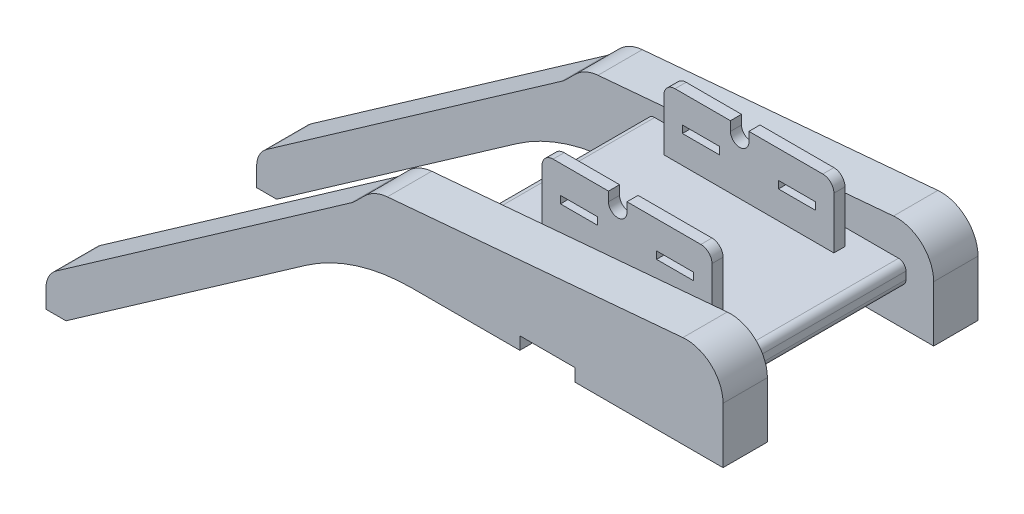
SolidWorks part; units mm, degrees
ref_plane "Front Plane" through (0, 0, 0) normal (0, 0, 1) x (1, 0, 0)
ref_plane "Top Plane" through (0, 0, 0) normal (0, 1, 0) x (1, 0, 0)
ref_plane "Right Plane" through (0, 0, 0) normal (1, 0, 0) x (0, 0, -1)
sketch "Sketch1" plane through (0, 0, 0) normal (0, 0, 1) x (1, 0, 0)
  line L1 (213.0197, -692.1049) -> (213.0197, -628.04)
  line L2 (248.221, -560.419) -> (1260.8984, 148.6653)
  line L3 (1277.8567, 162.8951) -> (1307.5066, 192.5449)
  line L5 (1470.2147, 0) -> (2540, 0)
  line L6 (2540, 0) -> (2540, 330.2)
  line L7 (1386.2404, 229.2591) -> (2540, 330.2)
  line L8 (281.5717, -692.1049) -> (1105.9937, -114.8385)
  line L9 (213.0197, -692.1049) -> (281.5717, -692.1049)
  arc A0 (1307.5066, 192.5449) -> (1386.2404, 229.2591) centre (1397.3091, 102.7424) cw
  arc A1 (1260.8984, 148.6653) -> (1277.8567, 162.8951) centre (1188.0541, 252.6976) ccw
  arc A2 (213.0197, -628.04) -> (248.221, -560.419) centre (295.5697, -628.04) cw
  arc A4 (1105.9937, -114.8385) -> (1470.2147, 0) centre (1470.2147, -635) cw
  point P13 (1270, 155.0384)
  point P18 (0, 0)
  point P22 (1270, 0)
  dimension "D8" = 127
  dimension "D9" = 82.55
  dimension "D12" = 635
  dimension "D1" = 1270
  dimension "D3" = 220
  dimension "D4" = 85
  dimension "D5" = 215
  dimension "D6" = 1270
  dimension "D7" = 330.2
  dimension "D11" = 127
extrude "Boss-Extrude1" add sketch "Sketch1" along normal blind 152.4
sketch "Sketch2" plane through (0, 0, 152.4) normal (0, 0, 1) x (1, 0, 0)
  line L0 (2540, 0) -> (2540, 330.2) construction
  line L1 (1841.5, -147.066) -> (2032, -147.066)
  line L2 (1841.5, -147.066) -> (1841.5, 43.434)
  line L3 (1841.5, 43.434) -> (2032, 43.434)
  line L4 (2032, -147.066) -> (2032, 43.434)
  line L5 (1841.5, -147.066) -> (2032, 43.434) construction
  line L6 (1841.5, 43.434) -> (2032, -147.066) construction
  line L7 (1470.2147, 0) -> (2540, 0) construction
  point P0 (1936.75, -51.816)
  dimension "D1" = 190.5
  dimension "D2" = 508
  dimension "D3" = 43.434
extrude "Cut-Extrude1" cut sketch "Sketch2" against normal blind 254
sketch "Sketch4" plane through (0, 0, 152.4) normal (0, 0, 1) x (1, 0, 0)
  line L0 (2540, 0) -> (2540, 330.2) construction
  line L1 (1581.15, 124.7896) -> (2419.35, 124.7896)
  line L2 (1555.75, 150.1896) -> (1555.75, 175.5896)
  line L3 (1581.15, 200.9896) -> (2419.35, 200.9896)
  line L4 (2444.75, 150.1896) -> (2444.75, 175.5896)
  line L5 (1555.75, 124.7896) -> (2444.75, 200.9896) construction
  line L6 (1555.75, 200.9896) -> (2444.75, 124.7896) construction
  line L8 (2540, 330.2) -> (1386.2404, 229.2591) construction
  arc A0 (2419.35, 124.7896) -> (2444.75, 150.1896) centre (2419.35, 150.1896) ccw
  arc A1 (2419.35, 200.9896) -> (2444.75, 175.5896) centre (2419.35, 175.5896) cw
  arc A2 (1581.15, 124.7896) -> (1555.75, 150.1896) centre (1581.15, 150.1896) cw
  arc A3 (1555.75, 175.5896) -> (1581.15, 200.9896) centre (1581.15, 175.5896) cw
  point P0 (2000.25, 162.8896)
  point P19 (1963.1202, 279.7296)
  dimension "D4" = 25.4
  dimension "D1" = 76.2
  dimension "D2" = 889
  dimension "D3" = 95.25
  dimension "D5" = 78.74
extrude "Boss-Extrude2" add sketch "Sketch4" along normal blind 571.5
ref_plane "Plane1" through (0, 0, 438.15) normal (0, 0, 1) x (1, 0, 0)
fillet "Fillet1" radius 127 1 edges at (2540, 330.2, 76.2)
mirror "Mirror1" about plane through (0, 0, 438.15) normal (0, 0, 1) of "Fillet1", "Cut-Extrude1", "Boss-Extrude1"
ref_plane "Plane2" through (0, 0, 247.65) normal (0, 0, 1) x (1, 0, 0)
sketch "Sketch8" plane through (0, 0, 247.65) normal (0, 0, 1) x (1, 0, 0)
  line L0 (2419.35, 200.9896) -> (1581.15, 200.9896) construction
  line L2 (1497.1384, 200.9896) -> (2375.4143, 200.9896) construction
  line L4 (1708.15, 200.9896) -> (1708.15, 378.7896)
  line L5 (1746.25, 416.8896) -> (2254.25, 416.8896)
  line L6 (2292.35, 378.7896) -> (2292.35, 200.9896)
  line L7 (1708.15, 200.9896) -> (2292.35, 200.9896)
  line L8 (1771.65, 321.6396) -> (1898.65, 321.6396)
  line L9 (1898.65, 321.6396) -> (1898.65, 296.2396)
  line L10 (1898.65, 296.2396) -> (1771.65, 296.2396)
  line L11 (1771.65, 296.2396) -> (1771.65, 321.6396)
  line L12 (2101.85, 321.6396) -> (2228.85, 321.6396)
  line L13 (2228.85, 321.6396) -> (2228.85, 296.2396)
  line L14 (2228.85, 296.2396) -> (2101.85, 296.2396)
  line L15 (2101.85, 296.2396) -> (2101.85, 321.6396)
  arc A0 (2254.25, 416.8896) -> (2292.35, 378.7896) centre (2254.25, 378.7896) cw
  arc A1 (1708.15, 378.7896) -> (1746.25, 416.8896) centre (1746.25, 378.7896) cw
  point P0 (1936.2763, 200.9896)
  dimension "D1" = 38.1
  dimension "D2" = 215.9
  dimension "D3" = 127
  dimension "D4" = 127
  dimension "D5" = 63.5
  dimension "D6" = 63.5
  dimension "D7" = 127
  dimension "D8" = 25.4
  dimension "D9" = 95.25
extrude "Boss-Extrude3" add sketch "Sketch8" against normal blind 38.1
sketch "Sketch9" plane through (0, 0, 247.65) normal (0, 0, 1) x (1, 0, 0)
  line L0 (1708.15, 378.7896) -> (1708.15, 200.9896) construction
  line L1 (1936.75, 385.1396) -> (1936.75, 416.8896)
  line L2 (1936.75, 416.8896) -> (2000.25, 416.8896)
  line L3 (2000.25, 416.8896) -> (2000.25, 385.1396)
  line L4 (2254.25, 416.8896) -> (1746.25, 416.8896) construction
  arc A0 (1936.75, 385.1396) -> (2000.25, 385.1396) centre (1968.5, 385.1396) ccw
  dimension "D1" = 63.5
  dimension "D3" = 228.6
  dimension "D2" = 31.75
extrude "Cut-Extrude2" cut sketch "Sketch9" against normal blind 43.18
mirror "Mirror2" about plane through (0, 0, 438.15) normal (0, 0, 1) of "Cut-Extrude2", "Boss-Extrude3"
